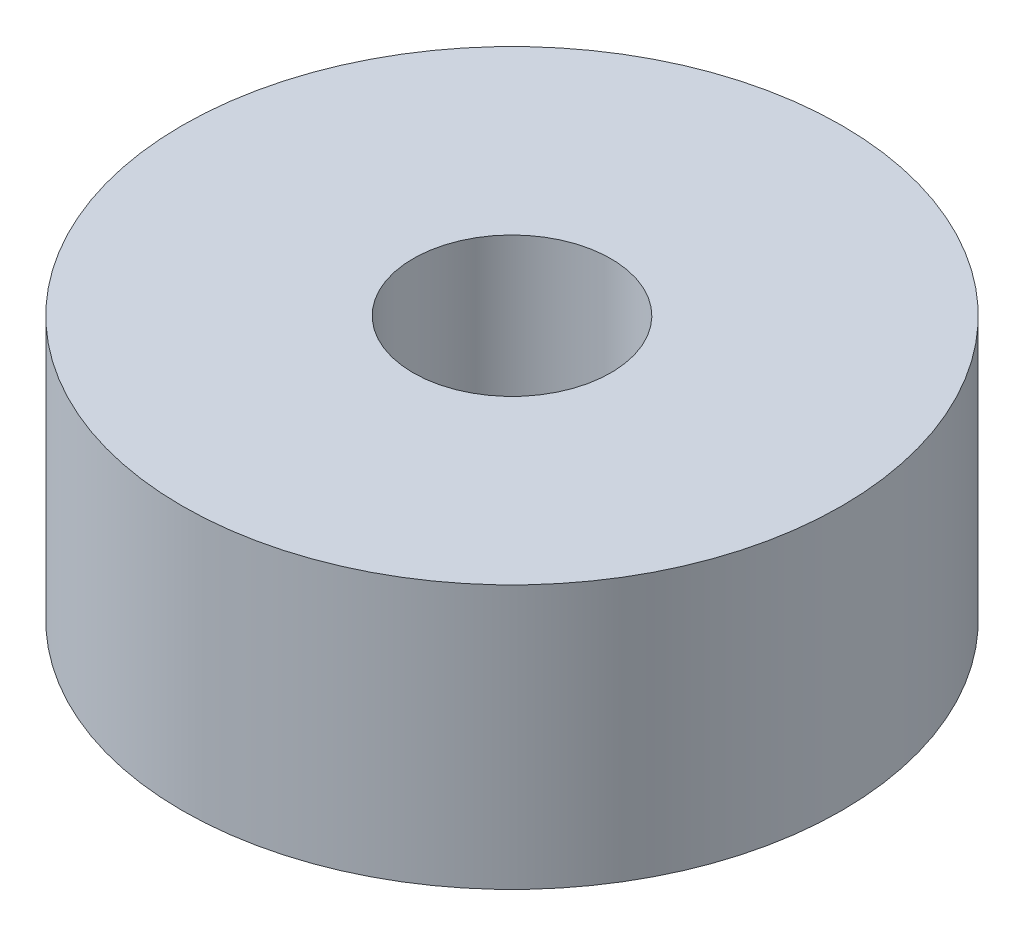
SolidWorks part; units mm, degrees
ref_plane "Front Plane" through (0, 0, 0) normal (0, 0, 1) x (1, 0, 0)
ref_plane "Top Plane" through (0, 0, 0) normal (0, 1, 0) x (1, 0, 0)
ref_plane "Right Plane" through (0, 0, 0) normal (1, 0, 0) x (0, 0, -1)
sketch "Sketch1" plane through (0, 0, 0) normal (0, 1, 0) x (1, 0, 0)
  circle A0 centre (0, 0) radius 1.5
  circle A1 centre (0, 0) radius 5
  dimension "D1" = 3
  dimension "D2" = 10
extrude "Boss-Extrude1" add sketch "Sketch1" along normal mid plane 4
